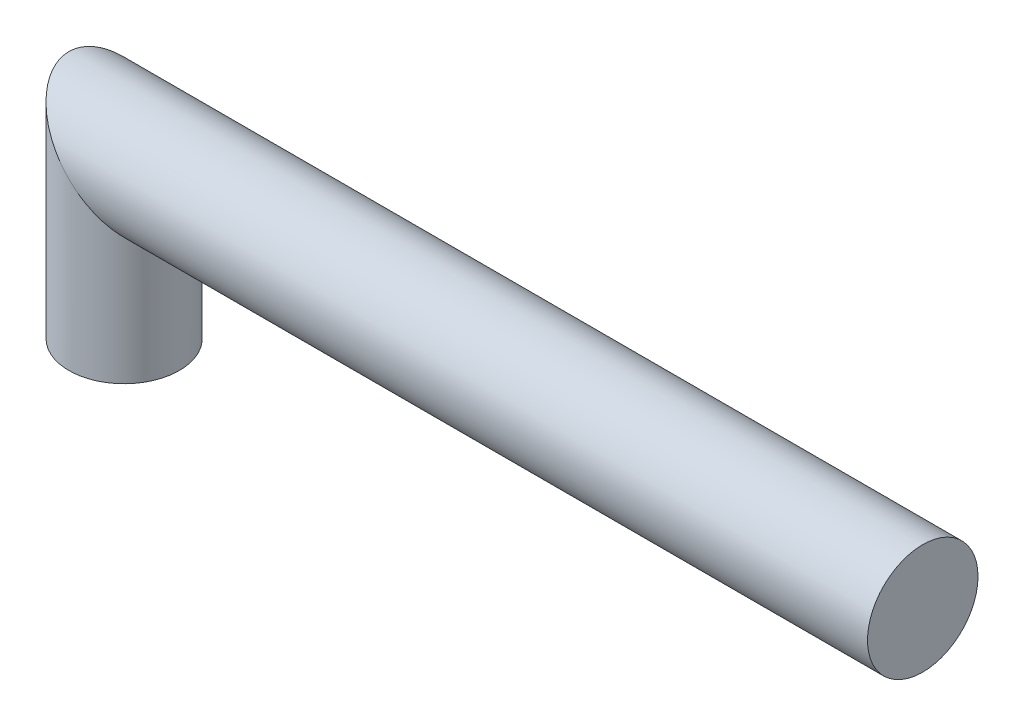
SolidWorks part; units mm, degrees
other "Markup1"
sketch "Sketch3" plane through (-52.73, -30, 10) normal (0, 0, 1) x (1, 0, 0)
ref_plane "Front Plane" through (0, 0, 0) normal (0, 0, 1) x (1, 0, 0)
ref_plane "Top Plane" through (0, 0, 0) normal (0, 1, 0) x (1, 0, 0)
ref_plane "Right Plane" through (0, 0, 0) normal (1, 0, 0) x (0, 0, -1)
ref_plane "Plane1" through (101.83, 0, 0) normal (1, 0, 0) x (0, 0, -1)
sketch "Sketch1" plane through (101.83, 0, 0) normal (1, 0, 0) x (0, 0, -1)
  circle A0 centre (0, 0) radius 10
sketch "Sketch2" plane through (0, 0, 0) normal (0, 0, 1) x (1, 0, 0)
  line L0 (101.83, 0) -> (-42.73, 0)
  line L1 (101.83, -10) -> (101.83, 10) construction
  line L2 (-42.73, 0) -> (-42.73, -30)
sweep "Sweep1" add profiles "Sketch1" path "Sketch2"
